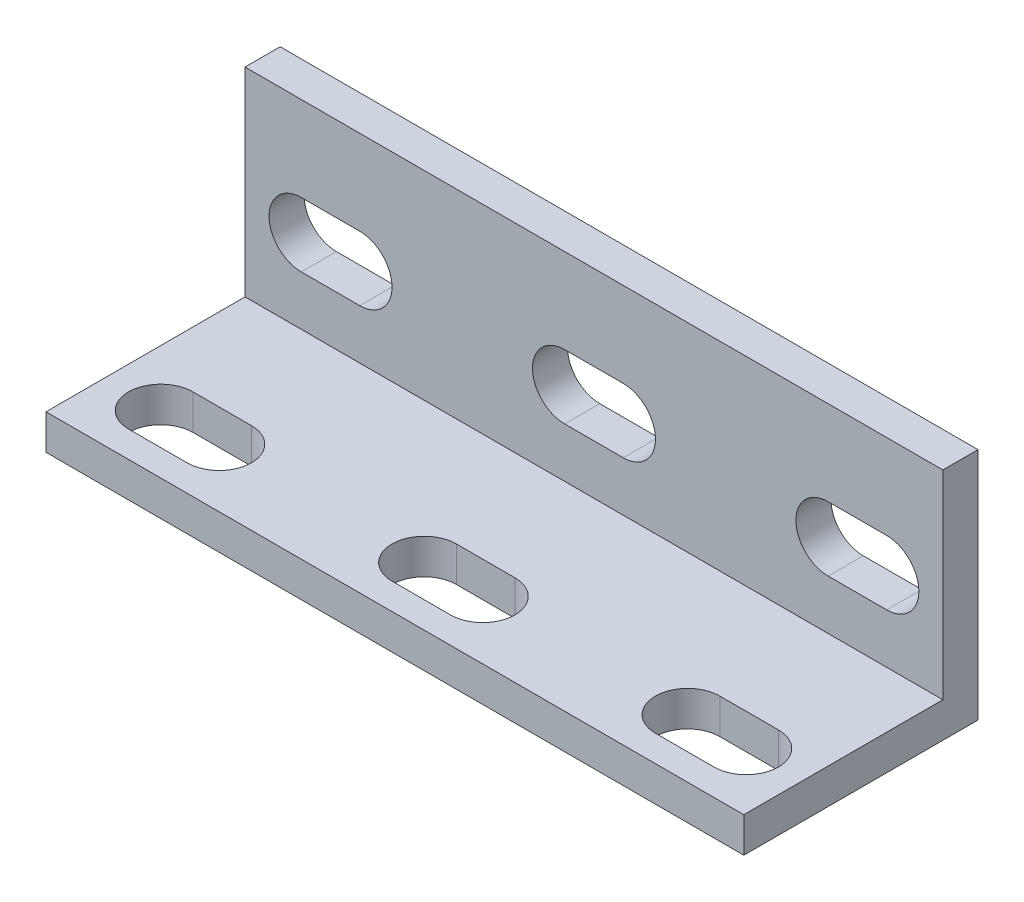
SolidWorks part; units mm, degrees
material "6063-T5"
ref_plane "Front Plane" through (0, 0, 0) normal (0, 0, 1) x (1, 0, 0)
ref_plane "Top Plane" through (0, 0, 0) normal (0, 1, 0) x (1, 0, 0)
ref_plane "Right Plane" through (0, 0, 0) normal (1, 0, 0) x (0, 0, -1)
sketch "Sketch2" plane through (0, 0, 0) normal (1, 0, 0) x (0, 0, -1)
  line L0 (0, 0) -> (0, 20)
  line L1 (0, 20) -> (-3, 20)
  line L2 (-3, 20) -> (-3, 3)
  line L3 (-3, 3) -> (-20, 3)
  line L4 (-20, 3) -> (-20, 0)
  line L5 (-20, 0) -> (0, 0)
  dimension "D1" = 20
  dimension "D2" = 3
  dimension "D3" = 20
  dimension "D4" = 3
extrude "Boss-Extrude1" add sketch "Sketch2" along normal mid plane 59.6
sketch "Sketch3" plane through (0, 3, 0) normal (0, 1, 0) x (1, 0, 0)
  line L0 (-2.5, -12.25) -> (2.5, -12.25)
  line L1 (-2.5, -17.75) -> (2.5, -17.75)
  line L2 (0, -12.25) -> (0, -17.75) construction
  line L3 (0.25, -15) -> (-0.25, -15) construction
  line L4 (29.8, -20) -> (-29.8, -20) construction
  line L5 (20, -12.25) -> (25, -12.25)
  line L6 (20, -17.75) -> (25, -17.75)
  line L7 (-25, -12.25) -> (-20, -12.25)
  line L8 (-25, -17.75) -> (-20, -17.75)
  arc A0 (2.5, -17.75) -> (2.5, -12.25) centre (2.5, -15) ccw
  arc A1 (-2.5, -12.25) -> (-2.5, -17.75) centre (-2.5, -15) ccw
  arc A2 (20, -12.25) -> (20, -17.75) centre (20, -15) ccw
  arc A3 (25, -17.75) -> (25, -12.25) centre (25, -15) ccw
  arc A4 (-25, -12.25) -> (-25, -17.75) centre (-25, -15) ccw
  arc A5 (-20, -17.75) -> (-20, -12.25) centre (-20, -15) ccw
  point P10 (0, -15)
  dimension "D1" = 5.5
  dimension "D2" = 5
  dimension "D3" = 2.25
  dimension "D4" = 2
  dimension "D5" = 2
extrude "Cut-Extrude1" cut sketch "Sketch3" against normal up to surface (3 mm away) up to face at (0, 0, 10)
sketch "Sketch5" plane through (0, 0, 3) normal (0, 0, 1) x (1, 0, 0)
  line L0 (2.5, 7.25) -> (-2.5, 7.25)
  line L1 (-2.5, 12.75) -> (2.5, 12.75)
  line L2 (5.25, 10) -> (-5.25, 10) construction
  line L3 (0, 7.25) -> (0, 12.75) construction
  line L4 (29.8, 20) -> (-29.8, 20) construction
  line L5 (20, 12.75) -> (25, 12.75)
  line L6 (25, 7.25) -> (20, 7.25)
  line L7 (-20, 7.25) -> (-25, 7.25)
  line L8 (-25, 12.75) -> (-20, 12.75)
  line L9 (-17.25, 10) -> (-27.75, 10) construction
  line L10 (-22.5, 7.25) -> (-22.5, 12.75) construction
  arc A0 (-2.5, 12.75) -> (-2.5, 7.25) centre (-2.5, 10) ccw
  arc A1 (2.5, 7.25) -> (2.5, 12.75) centre (2.5, 10) ccw
  arc A2 (20, 12.75) -> (20, 7.25) centre (20, 10) ccw
  arc A3 (25, 7.25) -> (25, 12.75) centre (25, 10) ccw
  arc A4 (-25, 12.75) -> (-25, 7.25) centre (-25, 10) ccw
  arc A5 (-20, 7.25) -> (-20, 12.75) centre (-20, 10) ccw
  dimension "D1" = 5.5
  dimension "D2" = 5
  dimension "D3" = 7.25
  dimension "D4" = 2
  dimension "D5" = 2
extrude "Cut-Extrude2" cut sketch "Sketch5" against normal up to surface (3 mm away) up to face at (0, 10, 0)
